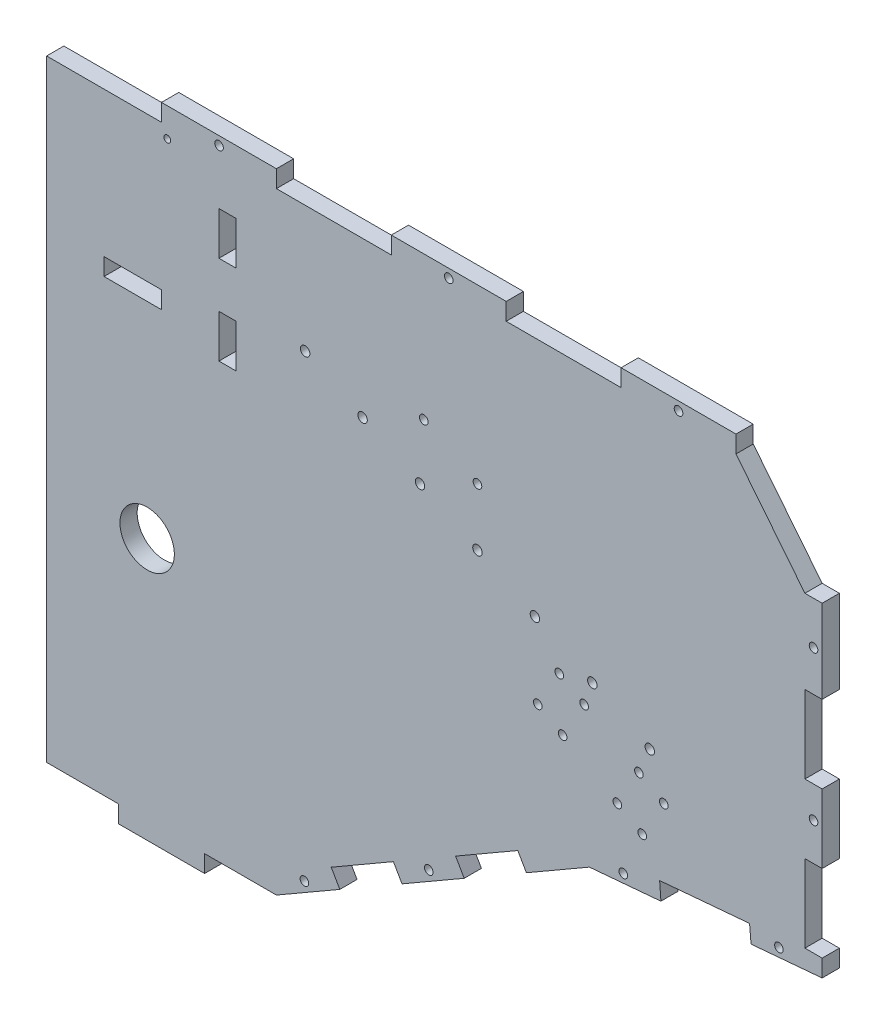
SolidWorks part; units mm, degrees
ref_plane "Plan de face" through (0, 0, 0) normal (0, 0, 1) x (1, 0, 0)
ref_plane "Plan de dessus" through (0, 0, 0) normal (0, 1, 0) x (1, 0, 0)
ref_plane "Plan de droite" through (0, 0, 0) normal (1, 0, 0) x (0, 0, -1)
sketch "Esquisse1" plane through (0, 0, 0) normal (0, 0, 1) x (1, 0, 0)
  line L1 (135, -106.5) -> (-135, -106.5)
  line L2 (135, -106.5) -> (135, 106.5)
  line L3 (135, 106.5) -> (-135, 106.5)
  line L4 (-135, -106.5) -> (-135, 106.5)
  line L5 (135, -106.5) -> (-135, 106.5) construction
  line L6 (135, 106.5) -> (-135, -106.5) construction
  point P0 (0, 0)
  dimension "D1" = 270
  dimension "D2" = 213
extrude "Boss.-Extru.1" add sketch "Esquisse1" along normal blind 6
sketch "Esquisse3" plane through (0, 0, 6) normal (0, 0, 1) x (1, 0, 0)
  line L0 (-135, -106.5) -> (135, -106.5) construction
  line L1 (-135, 106.5) -> (-135, -106.5) construction
  line L2 (-135, -106.5) -> (135, -106.5) construction
  circle A0 centre (-100, -21.5) radius 9.475
  circle A1 centre (43.4897, 9.5237) radius 1.5
  circle A2 centre (52.1499, 4.5237) radius 1.5
  circle A3 centre (35.9897, -3.4667) radius 1.5
  circle A4 centre (44.6499, -8.4667) radius 1.5
  circle A5 centre (63.7025, -19.4667) radius 1.5
  circle A6 centre (72.3627, -24.4667) radius 1.5
  circle A7 centre (79.8627, -11.4763) radius 1.5
  circle A8 centre (71.2025, -6.4763) radius 1.5
  dimension "D1" = 85
  dimension "D3" = 3
  dimension "D4" = 3
  dimension "D5" = 3
  dimension "D6" = 3
  dimension "D7" = 3
  dimension "D8" = 3
  dimension "D9" = 3
  dimension "D10" = 3
  dimension "D11" = 82.0333
  dimension "D12" = 3
  dimension "D13" = 18.95
  dimension "D2" = 35
extrude "Enlèv. mat.-Extru.1" cut sketch "Esquisse3" against normal blind 10
sketch "Esquisse5" plane through (0, 0, 6) normal (0, 0, 1) x (1, 0, 0)
  line L0 (53.9637, -43.5898) -> (135, -36.5)
  line L1 (53.9637, -43.5898) -> (-55, -106.5)
  line L3 (135, -106.5) -> (135, 106.5) construction
  line L4 (-135, -106.5) -> (135, -106.5) construction
  dimension "D1" = 80
  dimension "D2" = 95
  dimension "D3" = 0
  dimension "D4" = 150
  dimension "D5" = 70
  dimension "D6" = 0
extrude "Enlèv. mat.-Extru.11" cut sketch "Esquisse5" against normal through all and the other way through all
sketch "Esquisse6" plane through (0, 106.5, 0) normal (0, 1, 0) x (1, 0, 0)
  line L0 (135, -6) -> (-135, -6) construction
  line L1 (-55, -6) -> (-95, -6)
  line L2 (-55, -6) -> (-55, 0)
  line L3 (-55, 0) -> (-95, 0)
  line L4 (-95, -6) -> (-95, 0)
  line L5 (135, 0) -> (-135, 0) construction
  line L7 (-15, -6) -> (25, -6)
  line L8 (-15, -6) -> (-15, 0)
  line L9 (-15, 0) -> (25, 0)
  line L10 (25, -6) -> (25, 0)
  line L11 (105, -6) -> (65, -6)
  line L12 (105, -6) -> (105, 0)
  line L13 (105, 0) -> (65, 0)
  line L14 (65, -6) -> (65, 0)
  dimension "D1" = 40
  dimension "D2" = 40
  dimension "D3" = 40
  dimension "D4" = 40
  dimension "D5" = 40
  dimension "D6" = 40
extrude "Boss.-Extru.2" add sketch "Esquisse6" along normal blind 6
sketch "Esquisse7" plane through (0, 0, 0) normal (0, 0, -1) x (-1, 0, 0)
  line L1 (-135, -36.5) -> (-135, 106.5) construction
  line L2 (-135, 106.5) -> (-129, 106.5)
  line L3 (-135, 106.5) -> (-135, 76.5)
  line L4 (-135, 76.5) -> (-129, 76.5)
  line L6 (-129, 106.5) -> (-129, 76.5)
  line L7 (-135, 47.5) -> (-129, 47.5)
  line L8 (-135, 47.5) -> (-135, 20.5)
  line L9 (-135, 20.5) -> (-129, 20.5)
  line L10 (-129, 47.5) -> (-129, 20.5)
  line L12 (-135, -3.5) -> (-129, -3.5)
  line L13 (-135, -3.5) -> (-135, -30.5)
  line L14 (-135, -30.5) -> (-129, -30.5)
  line L15 (-129, -3.5) -> (-129, -30.5)
  dimension "D1" = 6
  dimension "D2" = 30
  dimension "D3" = 29
  dimension "D4" = 6
  dimension "D5" = 6
  dimension "D6" = 27
  dimension "D7" = 24
  dimension "D8" = 27
extrude "Enlèv. mat.-Extru.12" cut sketch "Esquisse7" against normal blind 6
sketch "Esquisse8" plane through (0, -106.5, 0) normal (0, -1, 0) x (1, 0, 0)
  line L0 (-135, 0) -> (-55, 0) construction
  line L1 (-80, 0) -> (-110, 0)
  line L2 (-80, 0) -> (-80, 6)
  line L3 (-80, 6) -> (-110, 6)
  line L4 (-110, 0) -> (-110, 6)
  line L5 (-135, 6) -> (-55, 6) construction
  dimension "D1" = 30
  dimension "D2" = 25
extrude "Boss.-Extru.3" add sketch "Esquisse8" along normal blind 6
sketch "Esquisse9" plane through (0, 0, 0) normal (0, 0, -1) x (-1, 0, 0)
  line L0 (-110.25, -38.6653) -> (-109.7271, -32.6882)
  line L1 (-53.9637, -43.5898) -> (-135, -36.5) construction
  line L3 (-78.8637, -41.4113) -> (-78.423, -35.4113)
  line L4 (-78.423, -35.4113) -> (-109.7271, -32.6882)
  line L5 (-110.25, -38.6653) -> (-78.8637, -41.4113)
  dimension "D1" = 90
  dimension "D2" = 6
  dimension "D3" = 24.9
  dimension "D4" = 24.75
  dimension "D5" = 6
extrude "Enlèv. mat.-Extru.13" cut sketch "Esquisse9" against normal through all
sketch "Esquisse10" plane through (0, 0, 0) normal (0, 0, -1) x (-1, 0, 0)
  line L0 (-32.0356, -56.25) -> (-10.3849, -68.75)
  line L1 (55, -106.5) -> (-53.9637, -43.5898) construction
  line L2 (-10.3849, -68.75) -> (-7.3849, -63.5538)
  line L3 (-7.3849, -63.5538) -> (-29.0356, -51.0538)
  line L4 (-29.0356, -51.0538) -> (-32.0356, -56.25)
  line L5 (11.2657, -81.25) -> (32.9164, -93.75)
  line L6 (32.9164, -93.75) -> (35.9164, -88.5538)
  line L7 (35.9164, -88.5538) -> (14.2657, -76.0538)
  line L8 (14.2657, -76.0538) -> (11.2657, -81.25)
  dimension "D1" = 6
  dimension "D2" = 6
  dimension "D3" = 25
  dimension "D4" = 25
  dimension "D5" = 25
  dimension "D6" = 25.5
extrude "Enlèv. mat.-Extru.14" cut sketch "Esquisse10" against normal blind 10
sketch "Esquisse11" plane through (0, 0, 0) normal (0, 0, -1) x (-1, 0, 0)
  line L0 (135, 106.5) -> (135, -106.5) construction
  line L1 (69, 59.5) -> (75, 59.5)
  line L2 (69, 59.5) -> (69, 44.5)
  line L3 (69, 44.5) -> (75, 44.5)
  line L4 (75, 59.5) -> (75, 44.5)
  line L5 (80, -106.5) -> (55, -106.5) construction
  line L7 (69, 90.5) -> (75, 90.5)
  line L8 (69, 90.5) -> (69, 75.5)
  line L9 (69, 75.5) -> (75, 75.5)
  line L10 (75, 90.5) -> (75, 75.5)
  dimension "D1" = 15
  dimension "D2" = 6
  dimension "D3" = 60
  dimension "D4" = 151
  dimension "D5" = 15
  dimension "D6" = 16
extrude "Enlèv. mat.-Extru.15" cut sketch "Esquisse11" against normal through all
sketch "Esquisse12" plane through (0, 0, 0) normal (0, 0, -1) x (-1, 0, 0)
  line L0 (-135, 47.5) -> (-135, 76.5) construction
  line L1 (-25, 112.5) -> (15, 112.5) construction
  line L2 (-105, 112.5) -> (-65, 112.5) construction
  line L3 (-135, -3.5) -> (-135, 20.5) construction
  line L4 (55, 112.5) -> (95, 112.5) construction
  line L6 (95, 112.5) -> (95, 106.5) construction
  circle A0 centre (5, 42.5) radius 1.65
  circle A1 centre (-15, 32.5) radius 1.65
  circle A2 centre (-35, 22.5) radius 1.65
  circle A3 centre (-55, 12.5) radius 1.65
  circle A4 centre (-75, 2.5) radius 1.65
  circle A5 centre (25, 52.5) radius 1.65
  circle A6 centre (45, 62.5) radius 1.65
  circle A7 centre (93, 102.5) radius 1.1852
  circle A8 centre (3.6753, 62.5) radius 1.5
  circle A9 centre (-15, 52.5) radius 1.5
  dimension "D1" = 3.3
  dimension "D4" = 3.3
  dimension "D5" = 3.3
  dimension "D6" = 3.3
  dimension "D7" = 3.3
  dimension "D8" = 80
  dimension "D9" = 120
  dimension "D10" = 90
  dimension "D11" = 100
  dimension "D12" = 100
  dimension "D13" = 80
  dimension "D14" = 60
  dimension "D15" = 110
  dimension "D16" = 3.3
  dimension "D17" = 3.3
  dimension "D18" = 160
  dimension "D19" = 60
  dimension "D20" = 180
  dimension "D21" = 50
  dimension "D22" = 10
  dimension "D23" = 2
  dimension "D24" = 3
  dimension "D25" = 3
  dimension "D2" = 140
  dimension "D3" = 70
extrude "Enlèv. mat.-Extru.16" cut sketch "Esquisse12" against normal through all
sketch "Esquisse13" plane through (0, 0, 0) normal (0, 0, -1) x (-1, 0, 0)
  line L0 (-129, 76.5) -> (-129, 106.5)
  line L1 (-129, 106.5) -> (-105, 106.5)
  line L2 (-105, 106.5) -> (-129, 76.5)
extrude "Enlèv. mat.-Extru.17" cut sketch "Esquisse13" against normal through all
sketch "Esquisse14" plane through (0, 0, 0) normal (0, 0, -1) x (-1, 0, 0)
  circle A0 centre (-75, 2.5) radius 4
  circle A1 centre (-55, 12.5) radius 4
  circle A2 centre (-35, 22.5) radius 4
  circle A3 centre (-15, 32.5) radius 4
  circle A4 centre (5, 42.5) radius 4
  circle A5 centre (25, 52.5) radius 4
  circle A6 centre (45, 62.5) radius 4
  dimension "D1" = 8
  dimension "D2" = 8
  dimension "D3" = 8
  dimension "D4" = 8
  dimension "D5" = 8
  dimension "D6" = 8
  dimension "D7" = 8
extrude "Enlèv. mat.-Extru.18" cut sketch "Esquisse14" against normal blind 1
sketch "Esquisse15" plane through (0, 0, 0) normal (0, 0, -1) x (-1, 0, 0)
  line L0 (-105, 112.5) -> (-65, 112.5) construction
  line L1 (14.2657, -76.0538) -> (11.2657, -81.25) construction
  line L2 (-25, 112.5) -> (-25, 106.5) construction
  line L3 (55, 112.5) -> (55, 106.5) construction
  line L4 (-135, -3.5) -> (-135, 20.5) construction
  line L5 (-135, 47.5) -> (-135, 76.5) construction
  line L6 (-53.9637, -43.5898) -> (-78.8637, -41.4113) construction
  line L7 (11.2657, -81.25) -> (-10.3849, -68.75) construction
  line L8 (55, -106.5) -> (32.9164, -93.75) construction
  line L10 (-78.8637, -41.4113) -> (-78.423, -35.4113) construction
  line L11 (35.9164, -88.5538) -> (32.9164, -93.75) construction
  line L12 (-110.25, -38.6653) -> (-135, -36.5) construction
  line L13 (-109.7271, -32.6882) -> (-110.25, -38.6653) construction
  circle A0 centre (-85, 109.5) radius 2.995
  circle A1 centre (-5, 109.5) radius 2.995
  circle A2 centre (75, 109.5) radius 2.995
  circle A3 centre (1.9404, -72.4019) radius 2.995
  circle A4 centre (-65.7671, -39.571) radius 2.995
  circle A5 centre (45.2417, -97.4019) radius 2.95
  circle A6 centre (-132, 9.5511) radius 2.995
  circle A7 centre (-132, 61.5795) radius 2.995
  circle A8 centre (-119.9505, -34.8052) radius 2.995
  point P8 (55, 109.5)
  point P10 (-25, 109.5)
  point P29 (-66.4137, -42.5005)
  point P42 (12.7657, -78.6519)
  dimension "D1" = 3
  dimension "D2" = 5.99
  dimension "D3" = 5.99
  dimension "D4" = 5.99
  dimension "D8" = 5.99
  dimension "D9" = 5.99
  dimension "D13" = 5.99
  dimension "D14" = 5.99
  dimension "D16" = 5.9
  dimension "D21" = 5.99
  dimension "D5" = 20
  dimension "D6" = 20
  dimension "D7" = 20
  dimension "D10" = 3
  dimension "D11" = 3
  dimension "D12" = 3
  dimension "D15" = 3
  dimension "D17" = 3
  dimension "D18" = 12.9266
  dimension "D19" = 12.5
  dimension "D20" = 12.5
  dimension "D22" = 3
  dimension "D23" = 10
extrude "Enlèv. mat.-Extru.19" cut sketch "Esquisse15" against normal blind 3
sketch "Esquisse16" plane through (0, 0, 0) normal (0, 0, -1) x (-1, 0, 0)
  circle A0 centre (-5, 109.5) radius 1.5
  circle A1 centre (74.9678, 109.5) radius 1.5
  circle A2 centre (-85, 109.5) radius 1.5
  circle A3 centre (-132, 61.5795) radius 1.5
  circle A4 centre (-132, 9.5511) radius 1.5
  circle A5 centre (-119.9505, -34.8052) radius 1.5
  circle A6 centre (-65.7671, -39.571) radius 1.5
  circle A7 centre (1.9404, -72.4019) radius 1.5
  circle A8 centre (45.2417, -97.4019) radius 1.5
extrude "Enlèv. mat.-Extru.20" cut sketch "Esquisse16" against normal blind 10
sketch "Esquisse17" plane through (0, 0, 0) normal (0, 0, -1) x (-1, 0, 0)
  line L0 (-105, 112.5) -> (-65, 112.5) construction
  line L1 (95, 56) -> (115, 56)
  line L2 (95, 56) -> (95, 50)
  line L3 (95, 50) -> (115, 50)
  line L4 (115, 56) -> (115, 50)
  line L6 (135, 106.5) -> (135, -106.5) construction
  dimension "D1" = 6
  dimension "D2" = 20
  dimension "D3" = 56.5
  dimension "D4" = 20
extrude "Enlèv. mat.-Extru.22" cut sketch "Esquisse17" against normal blind 10
